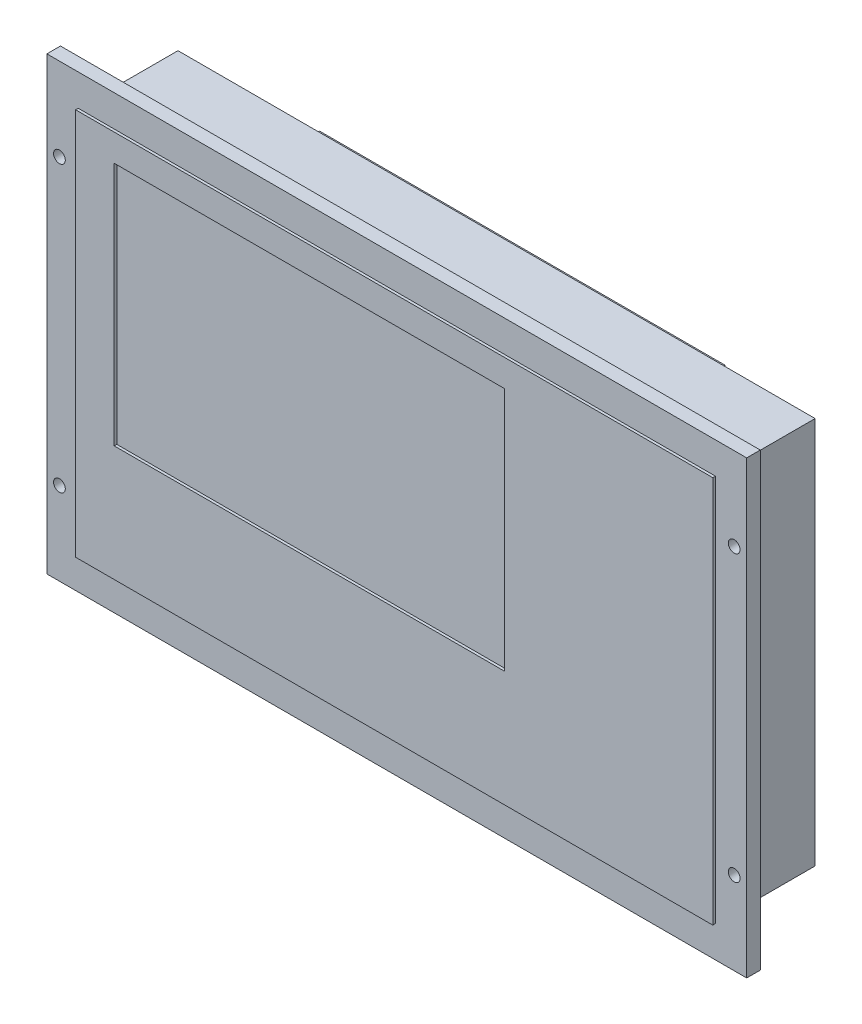
SolidWorks part; units mm, degrees
material "Nylon 6/10"
ref_plane "Front Plane" through (0, 0, 0) normal (0, 0, 1) x (1, 0, 0)
ref_plane "Top Plane" through (0, 0, 0) normal (0, 1, 0) x (1, 0, 0)
ref_plane "Right Plane" through (0, 0, 0) normal (1, 0, 0) x (0, 0, -1)
sketch "Sketch2" plane through (0, 0, 0) normal (0, 0, 1) x (1, 0, 0)
  line L1 (134, 86.25) -> (-134, 86.25)
  line L2 (134, 86.25) -> (134, -86.25)
  line L3 (134, -86.25) -> (-134, -86.25)
  line L4 (-134, 86.25) -> (-134, -86.25)
  line L5 (134, 86.25) -> (-134, -86.25) construction
  line L6 (134, -86.25) -> (-134, 86.25) construction
  point P0 (0, 0)
  dimension "D1" = 268
  dimension "D2" = 172.5
extrude "Boss-Extrude2" add sketch "Sketch2" along normal blind 5.2 separate body
sketch "Sketch1" plane through (0, 0, 0) normal (0, 0, 1) x (1, 0, 0)
  line L1 (122, -74.2) -> (-122, -74.2)
  line L2 (122, -74.2) -> (122, 74.2)
  line L3 (122, 74.2) -> (-122, 74.2)
  line L4 (-122, -74.2) -> (-122, 74.2)
  line L5 (122, -74.2) -> (-122, 74.2) construction
  line L6 (122, 74.2) -> (-122, -74.2) construction
  point P0 (0, 0)
  dimension "D1" = 244
  dimension "D2" = 148.4
extrude "Boss-Extrude1" add sketch "Sketch1" against normal blind 33 and the other way offset from surface (6.2 mm away) 1 other way up to face at (0, 0, 5.2)
hole_wizard "M4 Clearance Hole1" positions "Sketch3" profile "Sketch4" hole size "M4" standard "ANSI Metric" end condition up to next
sketch "Sketch3" plane through (0, 0, 0) normal (0, 0, -1) x (-1, 0, 0)
  line L1 (129.2, -54.5) -> (-129.2, -54.5)
  line L2 (129.2, -54.5) -> (129.2, 54.5)
  line L3 (129.2, 54.5) -> (-129.2, 54.5)
  line L4 (-129.2, -54.5) -> (-129.2, 54.5)
  line L5 (129.2, -54.5) -> (-129.2, 54.5) construction
  line L6 (129.2, 54.5) -> (-129.2, -54.5) construction
  point P2 (-129.2, 54.5)
  point P171 (129.2, -54.5)
  point P172 (129.2, 54.5)
  point P173 (-129.2, -54.5)
  point P186 (0, 0)
  dimension "D1" = 109
  dimension "D2" = 258.4
sketch "Sketch4" plane through (129.2, 54.5, 0) normal (1, 0, 0) x (0, 1, 0)
  line L0 (0, 0) -> (0, 5.2)
  line L1 (0, 5.2) -> (2.25, 5.2)
  line L2 (2.25, 5.2) -> (2.25, 0)
  line L5 (2.25, 0) -> (0, 0)
  line L11 (0, -6.35) -> (0, 107.95) construction
  dimension "Thru Hole Dia." = 4.5
  dimension "Thru Hole Depth" = 5.2
sketch "Sketch6" plane through (0, 0, 6.2) normal (0, 0, 1) x (1, 0, 0)
  line L1 (-107.2173, 63.8524) -> (42.3406, 63.8524)
  line L2 (-107.2173, 63.8524) -> (-107.2173, -29.8774)
  line L3 (-107.2173, -29.8774) -> (42.3406, -29.8774)
  line L4 (42.3406, 63.8524) -> (42.3406, -29.8774)
extrude "Cut-Extrude1" cut sketch "Sketch6" against normal up to surface (1 mm away) up to face at (126.95, 54.5, 5.2)
sketch "Sketch7" plane through (0, 0, -33) normal (0, 0, -1) x (-1, 0, 0)
  line L1 (-103.6716, 58.943) -> (-93.4688, 58.943)
  line L2 (-103.6716, 58.943) -> (-103.6716, -56.9599)
  line L3 (-103.6716, -56.9599) -> (-93.4688, -56.9599)
  line L4 (-93.4688, 58.943) -> (-93.4688, -56.9599)
  line L5 (-77.5526, 64.6565) -> (77.7328, 64.6565)
  line L6 (-77.5526, 64.6565) -> (-77.5526, 54.4538)
  line L7 (-77.5526, 54.4538) -> (77.7328, 54.4538)
  line L8 (77.7328, 64.6565) -> (77.7328, 54.4538)
  line L9 (-74.2877, -48.5937) -> (83.4463, -48.5937)
  line L10 (-74.2877, -48.5937) -> (-74.2877, -59.2045)
  line L11 (-74.2877, -59.2045) -> (83.4463, -59.2045)
  line L12 (83.4463, -48.5937) -> (83.4463, -59.2045)
extrude "Boss-Extrude3" add sketch "Sketch7" along normal blind 10
